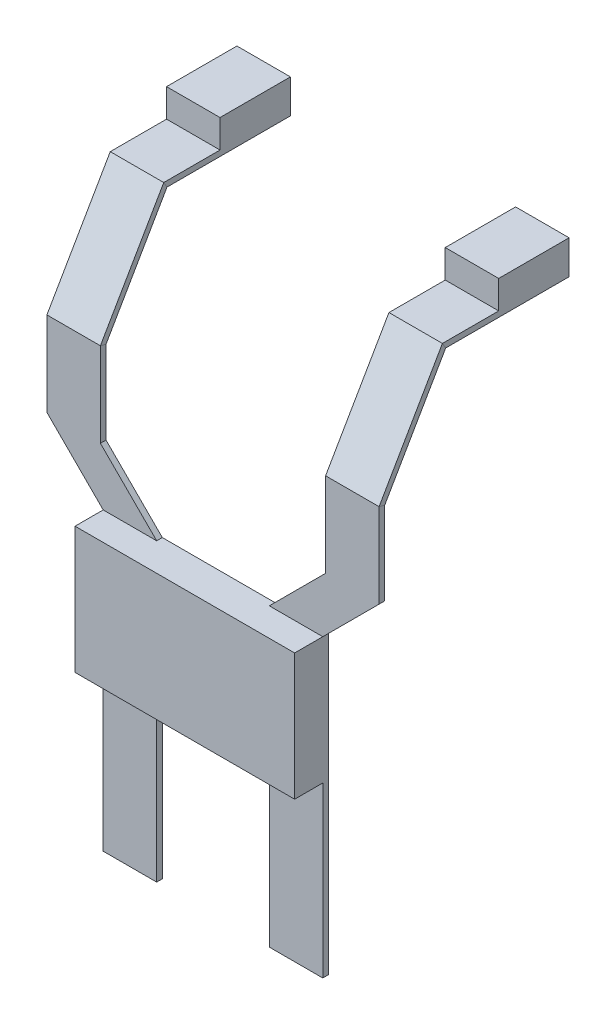
SolidWorks part; units mm, degrees
ref_plane "Front" through (0, 0, 0) normal (0, 0, 1) x (1, 0, 0)
ref_plane "Top" through (0, 0, 0) normal (0, 1, 0) x (1, 0, 0)
ref_plane "Right" through (0, 0, 0) normal (1, 0, 0) x (0, 0, -1)
sketch "草图1" plane through (0, 0, 0) normal (0, 0, 1) x (1, 0, 0)
  line L1 (0, 0) -> (0, -101.6526) construction
  line L2 (-40, 0) -> (40, 0)
  line L4 (-78, 0) -> (-78, 50)
  line L5 (-40, 50) -> (40, 50)
  line L6 (78, 0) -> (78, 50)
  line L8 (-78, 0) -> (-78, -160)
  line L9 (-78, -160) -> (-40, -160)
  line L10 (-40, 0) -> (-40, -160)
  line L12 (78, 0) -> (78, -160)
  line L13 (78, -160) -> (40, -160)
  line L14 (40, 0) -> (40, -160)
  line L15 (-143.4043, 90) -> (126.5484, 90) construction
  line L16 (-78, 50) -> (-118, 90)
  line L17 (-118, 90) -> (-80, 90)
  line L18 (-80, 90) -> (-40, 50)
  line L19 (78, 50) -> (118, 90)
  line L20 (118, 90) -> (80, 90)
  line L21 (80, 90) -> (40, 50)
  dimension "D1" = 156
  dimension "D2" = 78
  dimension "D3" = 50
  dimension "D4" = 160
  dimension "D5" = 38
  dimension "D6" = 38
  dimension "D7" = 40
  dimension "D8" = 38
  dimension "D9" = 38
extrude "凸台-拉伸1" add sketch "草图1" along normal blind 4
sketch "草图11" plane through (0, 0, 4) normal (0, 0, 1) x (1, 0, 0)
  line L0 (78, -160) -> (78, 50) construction
  line L1 (-78, 50) -> (78, 50)
  line L2 (-78, 50) -> (-78, -40)
  line L3 (-78, -40) -> (78, -40)
  line L4 (78, 50) -> (78, -40)
  dimension "D1" = 90
extrude "凸台-拉伸2" add sketch "草图11" along normal blind 20
sketch "草图12" plane through (0, 90, 0) normal (0, 1, 0) x (1, 0, 0)
  line L1 (-118, 0) -> (-80, 0)
  line L2 (-118, 0) -> (-118, -4)
  line L3 (-118, -4) -> (-80, -4)
  line L4 (-80, 0) -> (-80, -4)
  line L5 (118, 0) -> (80, 0)
  line L6 (118, 0) -> (118, -4)
  line L7 (118, -4) -> (80, -4)
  line L8 (80, 0) -> (80, -4)
sketch "草图13" plane through (78, 0, 0) normal (1, 0, 0) x (0, 0, -1)
  line L0 (-4, 90) -> (-4, 150)
  line L3 (-4, 150) -> (41, 227.9423)
  line L4 (41, 227.9423) -> (131, 227.9423)
  dimension "D1" = 60
  dimension "D2" = 150
  dimension "D3" = 90
  dimension "D5" = 90
sweep "扫描1" add profiles "草图12" path "草图13"
sketch "草图14" plane through (0, 227.9423, 0) normal (0, 1, 0) x (1, 0, 0)
  line L0 (-80, 41) -> (-80, 131) construction
  line L1 (-118, 131) -> (-80, 131)
  line L2 (-118, 131) -> (-118, 81)
  line L3 (-118, 81) -> (-80, 81)
  line L4 (-80, 131) -> (-80, 81)
  line L5 (80, 41) -> (80, 131) construction
  line L6 (118, 131) -> (80, 131)
  line L7 (118, 131) -> (118, 81)
  line L8 (118, 81) -> (80, 81)
  line L9 (80, 131) -> (80, 81)
  dimension "D1" = 50
  dimension "D2" = 50
extrude "凸台-拉伸3" add sketch "草图14" along normal blind 20
